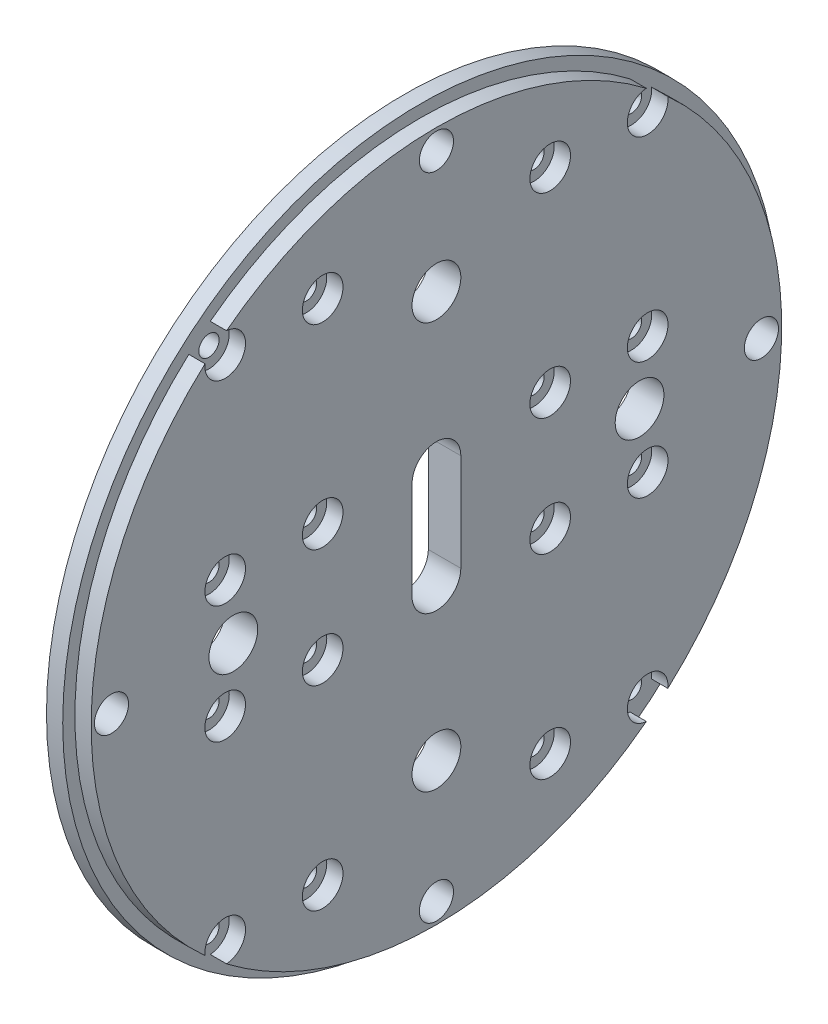
SolidWorks part; units mm, degrees
ref_plane "Alzado" through (0, 0, 0) normal (0, 0, 1) x (1, 0, 0)
ref_plane "Planta" through (0, 0, 0) normal (0, 1, 0) x (1, 0, 0)
ref_plane "Vista lateral" through (0, 0, 0) normal (1, 0, 0) x (0, 0, -1)
sketch "Croquis1" plane through (0, 0, 0) normal (1, 0, 0) x (0, 0, -1)
  line L0 (0, 0) -> (50000, 0) construction
  line L1 (0, 0) -> (0, 50000) construction
  circle A0 centre (0, 0) radius 44
  dimension "D1" = 88
extrude "Saliente-Extruir1" add sketch "Croquis1" along normal blind 4
sketch "Croquis2" plane through (0, 0, 0) normal (-1, 0, 0) x (0, 0, 1)
  line L0 (0, 0) -> (50000, 0) construction
  line L1 (0, 0) -> (0, 50000) construction
  circle A1 centre (14, 7.25) radius 1.25
  circle A2 centre (26, 7.25) radius 1.25
  circle A3 centre (26, 31.25) radius 1.25
  circle A4 centre (14, 31.25) radius 1.25
  circle A5 centre (-26, 31.25) radius 1.25
  circle A6 centre (-14, 31.25) radius 1.25
  circle A7 centre (-26, 7.25) radius 1.25
  circle A8 centre (-14, 7.25) radius 1.25
  circle A9 centre (-14, -7.25) radius 1.25
  circle A10 centre (-26, -7.25) radius 1.25
  circle A11 centre (-14, -31.25) radius 1.25
  circle A12 centre (-26, -31.25) radius 1.25
  circle A13 centre (14, -31.25) radius 1.25
  circle A14 centre (26, -31.25) radius 1.25
  circle A15 centre (26, -7.25) radius 1.25
  circle A16 centre (14, -7.25) radius 1.25
  dimension "D2" = 2.5
  dimension "D3" = 14.5
  dimension "D4" = 28
  dimension "D5" = 2
  dimension "D6" = 2
extrude "Cortar-Extruir2" cut sketch "Croquis2" against normal through all
sketch "Croquis3" plane through (0, 0, 0) normal (-1, 0, 0) x (0, 0, 1)
  line L0 (0, 0) -> (50000, 0) construction
  line L1 (0, 0) -> (0, 50000) construction
  circle A1 centre (14, 7.25) radius 2.5
  circle A2 centre (26, 7.25) radius 2.5
  circle A3 centre (26, 31.25) radius 2.5
  circle A4 centre (14, 31.25) radius 2.5
  circle A5 centre (-26, 31.25) radius 2.5
  circle A6 centre (-14, 31.25) radius 2.5
  circle A7 centre (-26, 7.25) radius 2.5
  circle A8 centre (-14, 7.25) radius 2.5
  circle A9 centre (-14, -7.25) radius 2.5
  circle A10 centre (-26, -7.25) radius 2.5
  circle A11 centre (-14, -31.25) radius 2.5
  circle A12 centre (-26, -31.25) radius 2.5
  circle A13 centre (14, -31.25) radius 2.5
  circle A14 centre (26, -31.25) radius 2.5
  circle A15 centre (26, -7.25) radius 2.5
  circle A16 centre (14, -7.25) radius 2.5
  dimension "D2" = 5
  dimension "D3" = 14.5
  dimension "D4" = 28
  dimension "D5" = 2
  dimension "D6" = 2
extrude "Cortar-Extruir3" cut sketch "Croquis3" against normal through all from offset 2 offset against normal yes
sketch "Croquis4" plane through (0, 0, 0) normal (-1, 0, 0) x (0, 0, 1)
  line L0 (0, 0) -> (50000, 0) construction
  line L1 (0, 0) -> (0, 50000) construction
  line L2 (0, 6) -> (0, -6) construction
  line L3 (3, 6) -> (3, -6)
  line L4 (-3, 6) -> (-3, -6)
  circle A0 centre (0, 25) radius 3
  circle A1 centre (25, 0) radius 3
  circle A2 centre (0, -25) radius 3
  circle A3 centre (-25, 0) radius 3
  arc A4 (3, 6) -> (-3, 6) centre (0, 6) ccw
  arc A5 (-3, -6) -> (3, -6) centre (0, -6) ccw
  point P9 (0, 0)
  point P16 (0, 0)
  dimension "D1" = 6
  dimension "D2" = 50
  dimension "D4" = 6
  dimension "D5" = 12
  dimension "D3" = 4
extrude "Cortar-Extruir4" cut sketch "Croquis4" against normal through all
sketch "Croquis5" plane through (4, 0, 0) normal (1, 0, 0) x (0, 0, -1)
  circle A0 centre (0, 0) radius 42.5
  circle A1 centre (0, 0) radius 44 construction
  dimension "D1" = 1.5
extrude "Cortar-Extruir5" cut sketch "Croquis5" against normal blind 2 flip side to cut
sketch "Croquis6" plane through (0, 0, 0) normal (-1, 0, 0) x (0, 0, 1)
  line L0 (0, 0) -> (50000, 0) construction
  line L1 (0, 0) -> (0, 50000) construction
  circle A0 centre (-40, 0) radius 2.1
  circle A1 centre (0, 0) radius 44 construction
  circle A2 centre (0, 40) radius 2.1
  circle A3 centre (40, 0) radius 2.1
  circle A4 centre (0, -40) radius 2.1
  point P18 (0, 0)
  dimension "D1" = 4.2
  dimension "D2" = 40
  dimension "D3" = 4
extrude "Cortar-Extruir6" cut sketch "Croquis6" against normal through all
